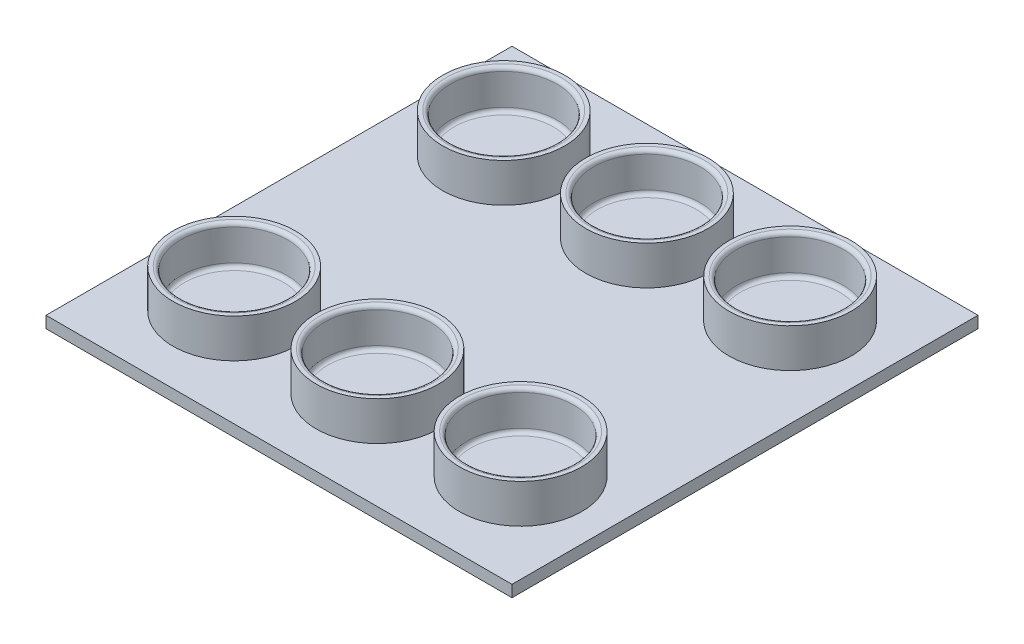
SolidWorks part; units mm, degrees
material "3.0205 (EN-AW 1200)"
ref_plane "Front Plane" through (0, 0, 0) normal (0, 0, 1) x (1, 0, 0)
ref_plane "Top Plane" through (0, 0, 0) normal (0, 1, 0) x (1, 0, 0)
ref_plane "Right Plane" through (0, 0, 0) normal (1, 0, 0) x (0, 0, -1)
sketch "Sketch3" plane through (0, 0, 0) normal (0, 1, 0) x (1, 0, 0)
  line L1 (-60, 60) -> (60, 60)
  line L2 (-60, 60) -> (-60, -60)
  line L3 (-60, -60) -> (60, -60)
  line L4 (60, 60) -> (60, -60)
  line L5 (-60, 60) -> (60, -60) construction
  line L6 (-60, -60) -> (60, 60) construction
  point P0 (0, 0)
  dimension "D1" = 120
  dimension "D2" = 120
extrude "Boss-Extrude1" add sketch "Sketch3" along normal blind 3
sketch "Sketch5" plane through (0, 3, 0) normal (0, 1, 0) x (1, 0, 0)
  circle A0 centre (0.1497, 34.5938) radius 13.75
  circle A1 centre (0.1497, -34.8146) radius 13.75
  circle A2 centre (37.0247, -34.8146) radius 13.75
  circle A3 centre (37.0247, 34.5938) radius 13.75
  circle A4 centre (-36.7303, -34.8146) radius 13.75
  circle A5 centre (-36.7303, 34.5938) radius 13.75
  circle A6 centre (0.1497, 34.5938) radius 15.75
  circle A7 centre (0.1497, -34.8146) radius 15.75
  circle A8 centre (37.0247, -34.8146) radius 15.75
  circle A9 centre (37.0247, 34.5938) radius 15.75
  circle A10 centre (-36.7303, -34.8146) radius 15.75
  circle A11 centre (-36.7303, 34.5938) radius 15.75
  dimension "D1" = 27.5
  dimension "D2" = 2
extrude "Boss-Extrude2" add sketch "Sketch5" along normal blind 10
fillet "Fillet2" radius 1 6 edges at (37.0247, 13, 21.0646) (37.0247, 3, -20.8438) (0.1497, 13, -20.8438) (0.1497, 3, 48.5646) (-36.7303, 3, 48.5646) (-36.7303, 13, -20.8438)
fillet "Fillet3" radius 1 6 edges at (-36.7303, 13, 21.0646) (0.1497, 13, 21.0646) (37.0247, 3, 48.5646) (37.0247, 13, -20.8438) (0.1497, 3, -20.8438) (-36.7303, 3, -20.8438)
